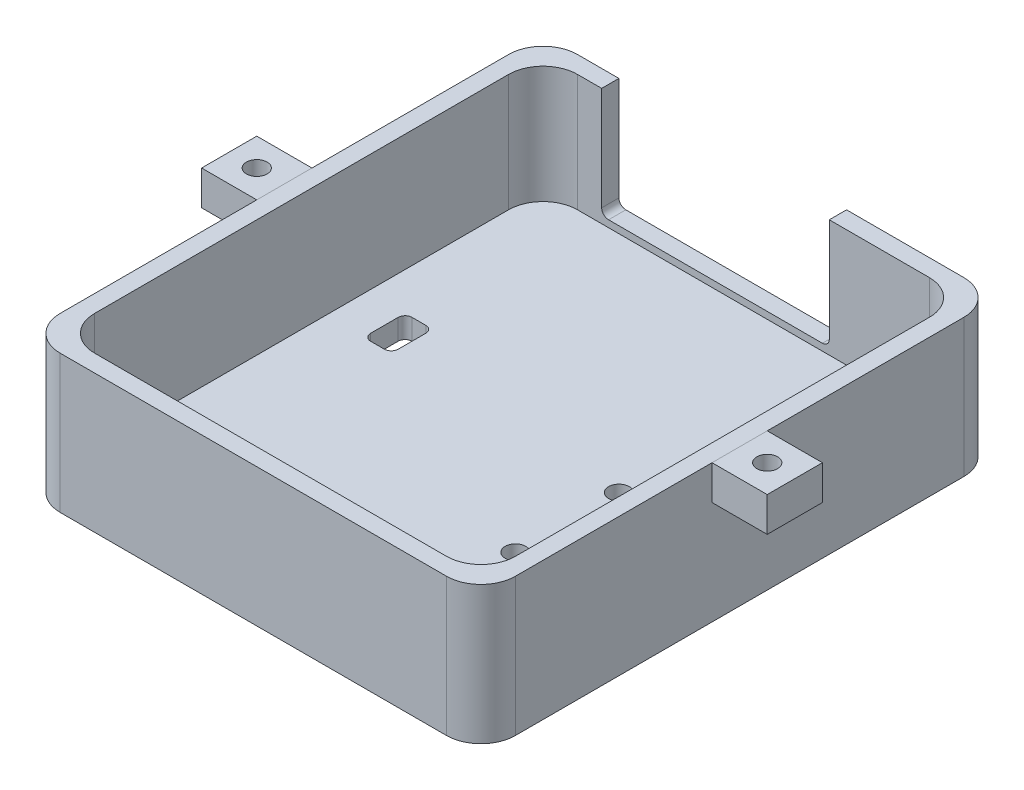
SolidWorks part; units mm, degrees
ref_plane "Ebene vorne" through (0, 0, 0) normal (0, 0, 1) x (1, 0, 0)
ref_plane "Ebene oben" through (0, 0, 0) normal (0, 1, 0) x (1, 0, 0)
ref_plane "Ebene rechts" through (0, 0, 0) normal (1, 0, 0) x (0, 0, -1)
sketch "Skizze1" plane through (0, 0, 0) normal (0, 1, 0) x (1, 0, 0)
  line L1 (28, -37.5) -> (-28, -37.5)
  line L2 (33, -32.5) -> (33, 32.5)
  line L3 (28, 37.5) -> (-28, 37.5)
  line L4 (-33, -32.5) -> (-33, 32.5)
  line L5 (33, -37.5) -> (-33, 37.5) construction
  line L6 (33, 37.5) -> (-33, -37.5) construction
  arc A0 (33, 32.5) -> (28, 37.5) centre (28, 32.5) ccw
  arc A1 (28, -37.5) -> (33, -32.5) centre (28, -32.5) ccw
  arc A2 (-28, -37.5) -> (-33, -32.5) centre (-28, -32.5) cw
  arc A3 (-28, 37.5) -> (-33, 32.5) centre (-28, 32.5) ccw
  point P0 (0, 0)
  dimension "D3" = 5
  dimension "D1" = 75
  dimension "D2" = 66
extrude "Aufsatz-Linear austragen1" add sketch "Skizze1" along normal blind 20
sketch "Skizze2" plane through (0, 20, 0) normal (0, 1, 0) x (1, 0, 0)
  line L0 (28, 37.5) -> (-28, 37.5) construction
  line L1 (25.5, -35) -> (-25.5, -35)
  line L2 (30.5, -30) -> (30.5, 30)
  line L3 (25.5, 35) -> (-25.5, 35)
  line L4 (-30.5, -30) -> (-30.5, 30)
  line L5 (30.5, -35) -> (-30.5, 35) construction
  line L6 (30.5, 35) -> (-30.5, -35) construction
  line L7 (33, -32.5) -> (33, 32.5) construction
  arc A0 (25.5, -35) -> (30.5, -30) centre (25.5, -30) ccw
  arc A1 (30.5, 30) -> (25.5, 35) centre (25.5, 30) ccw
  arc A2 (-25.5, 35) -> (-30.5, 30) centre (-25.5, 30) ccw
  arc A3 (-25.5, -35) -> (-30.5, -30) centre (-25.5, -30) cw
  point P0 (0, 0)
  dimension "D3" = 5
  dimension "D1" = 2.5
  dimension "D2" = 2.5
extrude "Schnitt-Linear austragen1" cut sketch "Skizze2" against normal blind 17
sketch "Skizze3" plane through (0, 0, -37.5) normal (0, 0, -1) x (-1, 0, 0)
  line L0 (-28, 0) -> (28, 0) construction
  line L1 (-10, 22) -> (21, 22)
  line L2 (-11, 21) -> (-11, 5)
  line L3 (-10, 4) -> (21, 4)
  line L4 (22, 21) -> (22, 5)
  line L5 (-11, 22) -> (22, 4) construction
  line L6 (-11, 4) -> (22, 22) construction
  line L7 (33, 20) -> (33, 0) construction
  arc A0 (21, 4) -> (22, 5) centre (21, 5) ccw
  arc A1 (-11, 5) -> (-10, 4) centre (-10, 5) ccw
  arc A2 (21, 22) -> (22, 21) centre (21, 21) cw
  arc A3 (-10, 22) -> (-11, 21) centre (-10, 21) ccw
  point P0 (5.5, 13)
  dimension "D5" = 1
  dimension "D1" = 4
  dimension "D2" = 11
  dimension "D3" = 33
  dimension "D4" = 18
extrude "Schnitt-Linear austragen2" cut sketch "Skizze3" against normal blind 32
sketch "Skizze4" plane through (0, 0, 0) normal (0, -1, 0) x (1, 0, 0)
  line L0 (28, -37.5) -> (-28, -37.5) construction
  line L1 (-22, -3.5) -> (-24, -3.5)
  line L2 (-21, -4.5) -> (-21, -8.5)
  line L3 (-22, -9.5) -> (-24, -9.5)
  line L4 (-25, -4.5) -> (-25, -8.5)
  line L5 (-21, -3.5) -> (-25, -9.5) construction
  line L6 (-21, -9.5) -> (-25, -3.5) construction
  line L7 (-33, -32.5) -> (-33, 32.5) construction
  arc A0 (-21, -8.5) -> (-22, -9.5) centre (-22, -8.5) cw
  arc A1 (-24, -9.5) -> (-25, -8.5) centre (-24, -8.5) cw
  arc A2 (-22, -3.5) -> (-21, -4.5) centre (-22, -4.5) cw
  arc A3 (-24, -3.5) -> (-25, -4.5) centre (-24, -4.5) ccw
  point P0 (-23, -6.5)
  dimension "D1" = 28
  dimension "D5" = 1
  dimension "D2" = 6
  dimension "D3" = 12
  dimension "D4" = 4
extrude "Schnitt-Linear austragen3" cut sketch "Skizze4" against normal blind 17
sketch "Skizze5" plane through (0, 0, 0) normal (0, -1, 0) x (1, 0, 0)
  line L1 (33, 32.5) -> (33, -32.5) construction
  line L2 (-28, 37.5) -> (28, 37.5) construction
  circle A0 centre (13, -2.5) radius 1.5
  circle A2 centre (13, 27.5) radius 1.5
  circle A4 centre (13, 12.5) radius 1.5
  dimension "D1" = 3
  dimension "D2" = 15
  dimension "D4" = 20
  dimension "D7" = 10
  dimension "D5" = 20
  dimension "D3" = 15
  dimension "D6" = 40
extrude "Schnitt-Linear austragen4" cut sketch "Skizze5" against normal blind 17
sketch "Skizze7" plane through (0, 20, 0) normal (0, 1, 0) x (1, 0, 0)
  line L4 (33, -4) -> (41, -4)
  line L5 (33, -4) -> (33, 4)
  line L6 (33, 4) -> (41, 4)
  line L7 (41, -4) -> (41, 4)
  line L8 (-28, -37.5) -> (28, -37.5) construction
  line L9 (33, -32.5) -> (33, 32.5) construction
  line L10 (-33, 32.5) -> (-33, -32.5) construction
  line L11 (-33, -4) -> (-41, -4)
  line L12 (-33, -4) -> (-33, 4)
  line L13 (-33, 4) -> (-41, 4)
  line L14 (-41, -4) -> (-41, 4)
  dimension "D1" = 8
  dimension "D2" = 8
  dimension "D3" = 8
  dimension "D4" = 8
  dimension "D5" = 33.5
  dimension "D6" = 33.5
extrude "Aufsatz-Linear austragen2" add sketch "Skizze7" against normal blind 5 separate body
sketch "Skizze8" plane through (0, 20, 0) normal (0, 1, 0) x (1, 0, 0)
  line L0 (-41, 4) -> (-41, -4) construction
  line L1 (-41, -4) -> (-33, -4) construction
  circle A0 centre (-37, 0) radius 1.5
  dimension "D1" = 3
  dimension "D2" = 4
  dimension "D3" = 4
extrude "Schnitt-Linear austragen6" cut sketch "Skizze8" against normal blind 10
sketch "Skizze9" plane through (0, 20, 0) normal (0, 1, 0) x (1, 0, 0)
  line L0 (33, -32.5) -> (33, 32.5) construction
  line L1 (41, 4) -> (33, 4) construction
  circle A0 centre (37, 0) radius 1.5
  dimension "D1" = 3
  dimension "D2" = 4
  dimension "D3" = 4
extrude "Schnitt-Linear austragen7" cut sketch "Skizze9" against normal blind 10
